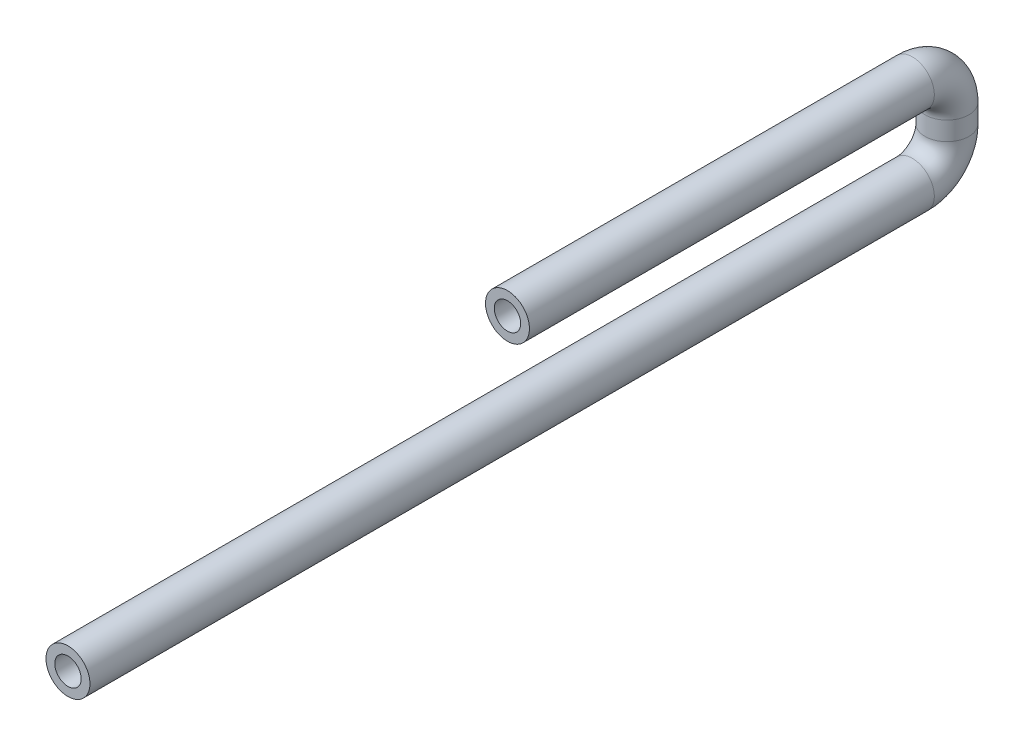
SolidWorks part; units mm, degrees
ref_plane "Front Plane" through (0, 0, 0) normal (0, 0, 1) x (1, 0, 0)
ref_plane "Top Plane" through (0, 0, 0) normal (0, 1, 0) x (1, 0, 0)
ref_plane "Right Plane" through (0, 0, 0) normal (1, 0, 0) x (0, 0, -1)
sketch "Sketch13" plane through (0, 0, 0) normal (0, 0, 1) x (1, 0, 0)
  circle A0 centre (-0.8302, -5.1832) radius 3.81
  circle A1 centre (-0.8302, -5.1832) radius 6.35
  dimension "D1" = 7.62
  dimension "D2" = 12.7
sketch "Sketch14" plane through (0, 0, 0) normal (1, 0, 0) x (0, 0, -1)
  line L0 (0, -5.1832) -> (117, -5.1832)
  line L1 (0, 1.1668) -> (0, -11.5332) construction
  line L2 (127, -15.1832) -> (127, -20.5832)
  line L3 (117, -30.5832) -> (-127, -30.5832)
  arc A0 (127, -15.1832) -> (117, -5.1832) centre (117, -15.1832) ccw
  arc A1 (117, -30.5832) -> (127, -20.5832) centre (117, -20.5832) ccw
  point P8 (127, -5.1832)
  point P11 (127, -30.5832)
  dimension "D4" = 10
  dimension "D5" = 10
  dimension "D1" = 127
  dimension "D2" = 25.4
  dimension "D3" = 254
sweep "Sweep1" add profiles "Sketch13" path "Sketch14"
